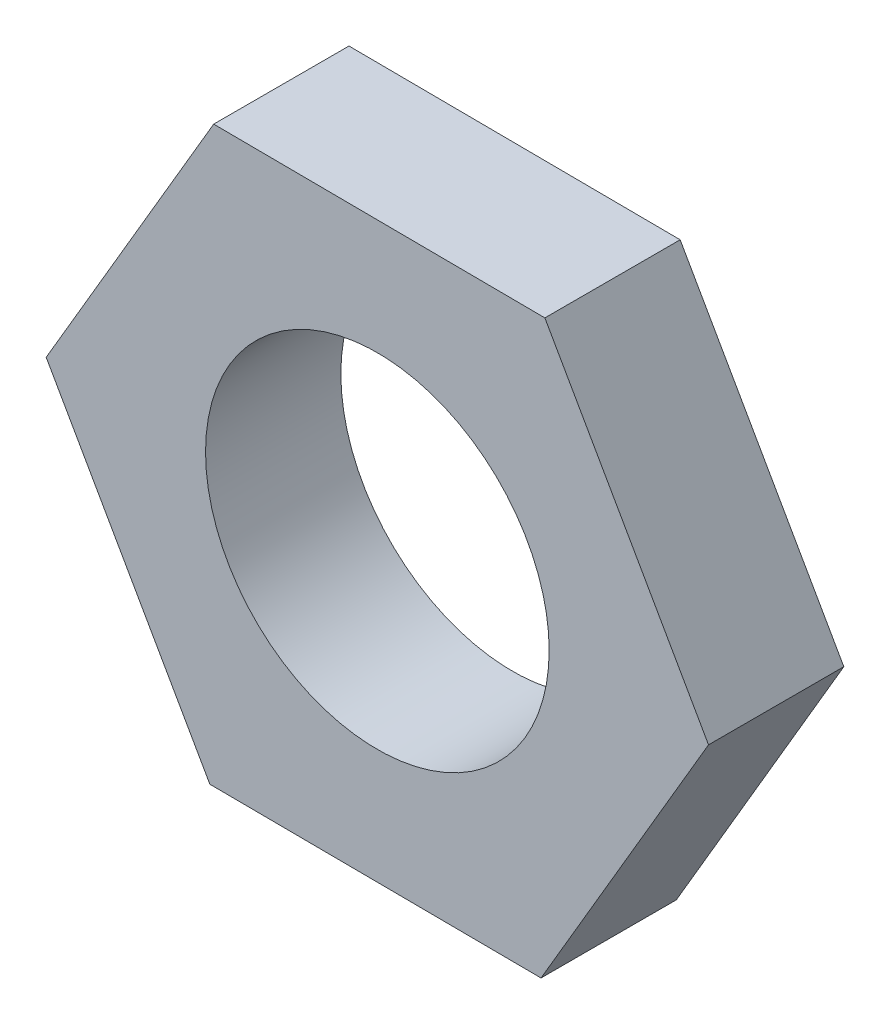
SolidWorks part; units mm, degrees
ref_plane "Front Plane" through (0, 0, 0) normal (0, 0, 1) x (1, 0, 0)
ref_plane "Top Plane" through (0, 0, 0) normal (0, 1, 0) x (1, 0, 0)
ref_plane "Right Plane" through (0, 0, 0) normal (1, 0, 0) x (0, 0, -1)
sketch "Sketch1" plane through (0, 0, 0) normal (0, 0, 1) x (1, 0, 0)
  line L1 (3.0243, -5.3205) -> (6.1198, -0.0411)
  line L2 (6.1198, -0.0411) -> (3.0955, 5.2793)
  line L3 (3.0955, 5.2793) -> (-3.0243, 5.3205)
  line L4 (-3.0243, 5.3205) -> (-6.1198, 0.0411)
  line L5 (-6.1198, 0.0411) -> (-3.0955, -5.2793)
  line L6 (-3.0955, -5.2793) -> (3.0243, -5.3205)
  circle A0 centre (0, 0) radius 3.175
  circle A1 centre (0, 0) radius 5.3 construction
  dimension "D1" = 6.35
extrude "Boss-Extrude1" add sketch "Sketch1" along normal blind 2.5
